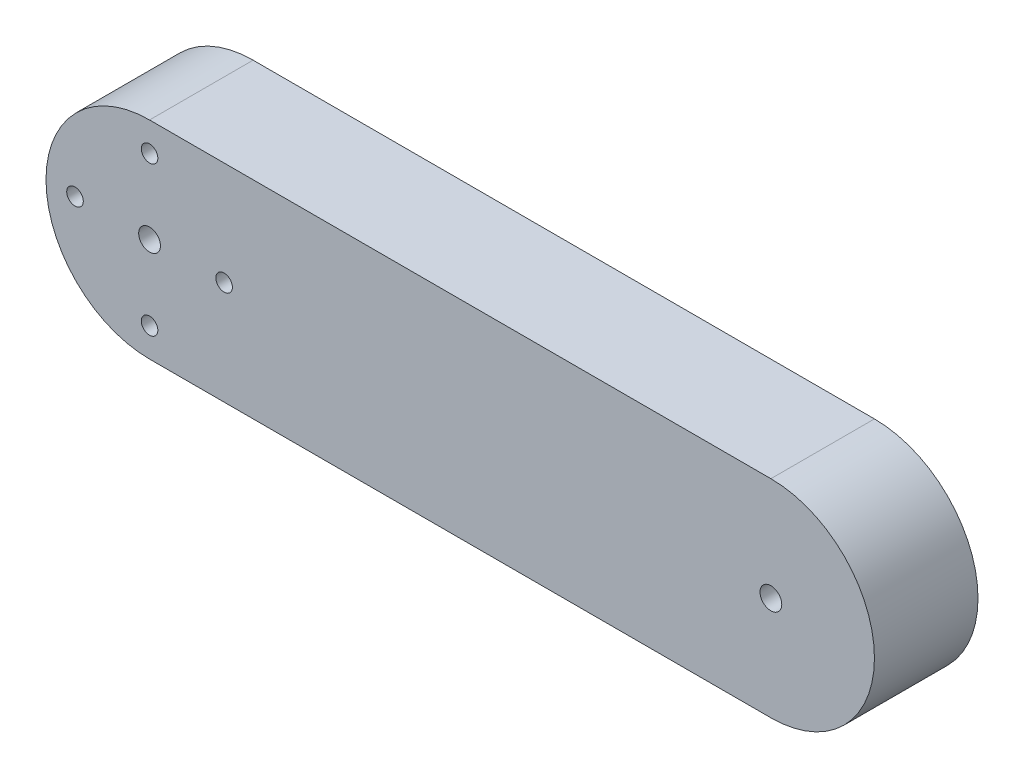
SolidWorks part; units mm, degrees
ref_plane "正面" through (0, 0, 0) normal (0, 0, 1) x (1, 0, 0)
ref_plane "平面" through (0, 0, 0) normal (0, 1, 0) x (1, 0, 0)
ref_plane "右側面" through (0, 0, 0) normal (1, 0, 0) x (0, 0, -1)
sketch "ｽｹｯﾁ2" plane through (0, 0, 0) normal (0, 0, 1) x (1, 0, 0)
  line L1 (-30, 10) -> (30, 10)
  line L2 (-30, 10) -> (-30, -10)
  line L3 (-30, -10) -> (30, -10)
  line L4 (30, 10) -> (30, -10)
  line L5 (-30, 10) -> (30, -10) construction
  line L6 (-30, -10) -> (30, 10) construction
  circle A0 centre (-30, 0) radius 10
  circle A1 centre (30, 0) radius 10
  circle A2 centre (-30, 0) radius 1.05
  circle A3 centre (30, 0) radius 1.05
  point P0 (0, 0)
  dimension "D3" = 2.1
  dimension "D4" = 2.1
  dimension "D1" = 20
  dimension "D2" = 60
extrude "ﾎﾞｽ - 押し出し1" add sketch "ｽｹｯﾁ2" along normal blind 10 contours A2 L2 A0 | A2 L2 A0 | A1 L1 A0 L3 | A3 L4 A1 | A3 L4 A1
hole_wizard "M2x0.4 ねじ穴1" positions "ｽｹｯﾁ3" profile "ｽｹｯﾁ4" tap size "M2x0.4" standard "JIS" end condition through all
sketch "ｽｹｯﾁ3" plane through (0, 0, 10) normal (0, 0, 1) x (1, 0, 0)
  circle A0 centre (-30, 0) radius 1.05
  point P0 (-30, 7.2)
  point P2 (-37.2, 0)
  point P4 (-37.2, 0)
  point P6 (-30, -7.2)
  dimension "D1" = 7.2
  dimension "D2" = 0
  dimension "D3" = 7.2
  dimension "D4" = 0
  dimension "D5" = 7.2
  dimension "D6" = 7.2
sketch "ｽｹｯﾁ4" plane through (-30, 7.2, 10) normal (1, 0, 0) x (0, -1, 0)
  line L0 (0, 0) -> (0, 10)
  line L1 (0, 10) -> (0.8, 10)
  line L2 (0.8, 10) -> (0.8, 0)
  line L5 (0.8, 0) -> (0, 0)
  line L11 (0, -6.35) -> (0, 107.95) construction
  dimension "次ｻｰﾌｪｽまでのねじ下穴ﾄﾞﾘﾙ直径" = 1.6
  dimension "次ｻｰﾌｪｽまでのねじ下穴ﾄﾞﾘﾙの深さ" = 10
cosmetic thread "穴のねじ山1" parameters "D2"=2
cosmetic thread "穴のねじ山2" parameters "D2"=2
cosmetic thread "穴のねじ山3" parameters "D2"=2
cosmetic thread "穴のねじ山4" parameters "D2"=2
hole_wizard "M2x0.4 ねじ穴2" positions "ｽｹｯﾁ5" profile "ｽｹｯﾁ6" tap size "M2x0.4" standard "JIS" end condition through all
sketch "ｽｹｯﾁ5" plane through (0, 0, 10) normal (0, 0, 1) x (1, 0, 0)
  circle A0 centre (-30, 0) radius 1.05
  point P0 (-22.8, 0)
  dimension "D1" = 7.2
sketch "ｽｹｯﾁ6" plane through (-22.8, 0, 10) normal (1, 0, 0) x (0, -1, 0)
  line L0 (0, 0) -> (0, 10)
  line L1 (0, 10) -> (0.8, 10)
  line L2 (0.8, 10) -> (0.8, 0)
  line L5 (0.8, 0) -> (0, 0)
  line L11 (0, -6.35) -> (0, 107.95) construction
  dimension "次ｻｰﾌｪｽまでのねじ下穴ﾄﾞﾘﾙ直径" = 1.6
  dimension "次ｻｰﾌｪｽまでのねじ下穴ﾄﾞﾘﾙの深さ" = 10
cosmetic thread "穴のねじ山5" parameters "D2"=2
